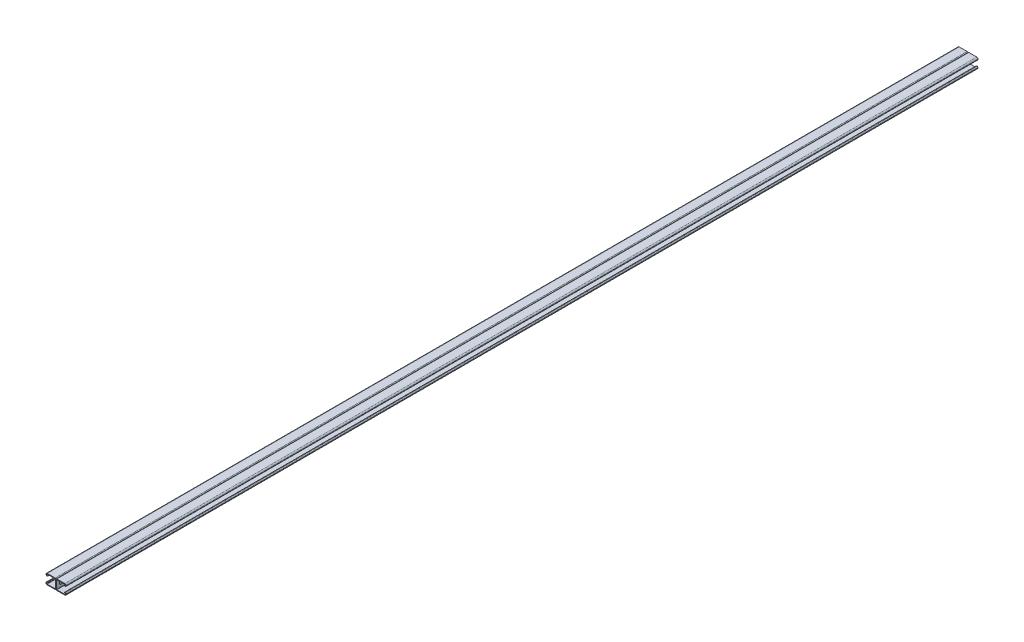
SolidWorks part; units mm, degrees
material "AISI 304"
ref_plane "Front Plane" through (0, 0, 0) normal (0, 0, 1) x (1, 0, 0)
ref_plane "Top Plane" through (0, 0, 0) normal (0, 1, 0) x (1, 0, 0)
ref_plane "Right Plane" through (0, 0, 0) normal (1, 0, 0) x (0, 0, -1)
sketch "Sketch1" plane through (0, 0, 0) normal (0, 0, 1) x (1, 0, 0)
  line L0 (0, 0) -> (-41.275, 0) construction
  line L3 (-41.275, 20.6375) -> (0, 20.6375) construction
  line L4 (-41.275, 20.6375) -> (-41.275, -20.6375) construction
  line L5 (-41.275, -20.6375) -> (0, -20.6375) construction
  line L6 (0, 20.6375) -> (0, -20.6375) construction
  line L7 (-36.2267, 20.6375) -> (-3.4607, 20.6375)
  line L8 (0, 17.1767) -> (0, -17.1767)
  line L9 (-2.794, -17.1767) -> (-2.794, 17.1767)
  line L10 (-3.4607, 17.8435) -> (-36.2267, 17.8435)
  line L11 (-41.275, 15.5892) -> (-41.275, 14.5732)
  line L12 (-37.8142, 11.1125) -> (-35.5346, 11.1125)
  line L14 (-35.5346, 13.9065) -> (-37.8142, 13.9065)
  line L15 (-38.481, 14.5732) -> (-38.481, 15.5892)
  line L16 (-38.481, -14.5733) -> (-38.481, -15.5893)
  line L17 (-35.5346, -13.9065) -> (-37.8142, -13.9065)
  line L18 (-37.8142, -11.1125) -> (-35.5346, -11.1125)
  line L19 (-41.275, -15.5893) -> (-41.275, -14.5733)
  line L20 (-3.4607, -17.8435) -> (-36.2267, -17.8435)
  line L21 (-36.2267, -20.6375) -> (-3.4607, -20.6375)
  line L22 (-2.794, -20.6375) -> (-2.794, 20.6375) construction
  arc A1 (0, 17.1767) -> (-3.4607, 20.6375) centre (-3.4607, 17.1767) ccw
  arc A2 (-2.794, 17.1767) -> (-3.4607, 17.8435) centre (-3.4607, 17.1767) ccw
  arc A4 (-36.2267, 20.6375) -> (-41.275, 15.5892) centre (-36.2267, 15.5892) ccw
  arc A5 (-41.275, 14.5732) -> (-37.8142, 11.1125) centre (-37.8142, 14.5732) ccw
  arc A6 (-35.5346, 11.1125) -> (-35.5346, 13.9065) centre (-35.5346, 12.5095) ccw
  arc A7 (-37.8142, 13.9065) -> (-38.481, 14.5732) centre (-37.8142, 14.5732) cw
  arc A8 (-38.481, 15.5892) -> (-36.2267, 17.8435) centre (-36.2267, 15.5892) cw
  arc A9 (-38.481, -15.5893) -> (-36.2267, -17.8435) centre (-36.2267, -15.5893) ccw
  arc A10 (-37.8142, -13.9065) -> (-38.481, -14.5733) centre (-37.8142, -14.5733) ccw
  arc A11 (-35.5346, -11.1125) -> (-35.5346, -13.9065) centre (-35.5346, -12.5095) cw
  arc A12 (-41.275, -14.5733) -> (-37.8142, -11.1125) centre (-37.8142, -14.5733) cw
  arc A13 (-36.2267, -20.6375) -> (-41.275, -15.5893) centre (-36.2267, -15.5893) cw
  arc A14 (-2.794, -17.1767) -> (-3.4607, -17.8435) centre (-3.4607, -17.1767) cw
  arc A15 (0, -17.1767) -> (-3.4607, -20.6375) centre (-3.4607, -17.1767) cw
  point P24 (0, 20.6375)
  point P65 (-2.794, 0)
  dimension "D1" = 3.4608
  dimension "D2" = 5.0482
  dimension "D3" = 3.4608
  dimension "Ht." = 41.275
  dimension "Wd." = 41.275
  dimension "Thk." = 2.794
  dimension "D4" = 9.525
  dimension "D5" = 7.1374
extrude "Boss-Extrude1" add sketch "Sketch1" against normal blind 3759.2
sketch "Sketch3" plane through (0, 0, 0) normal (1, 0, 0) x (0, 0, -1)
  line L0 (0, 0) -> (3759.2, 0) construction
  point P2 (101.6, 0)
  point P3 (3657.6, 0)
  dimension "D1" = 101.6
  dimension "D2" = 101.6
  dimension "D3" = 3759.2
sketch "Sketch2" plane through (0, 0, 0) normal (1, 0, 0) x (0, 0, -1)
  line L0 (18.2562, 0) -> (32.5437, 0) construction
  line L1 (18.2562, 7.1437) -> (32.5437, 7.1437)
  line L2 (18.2562, -7.1437) -> (32.5437, -7.1437)
  line L3 (18.2562, 0) -> (0, 0) construction
  line L4 (25.4, 0) -> (76.2, 0) construction
  line L5 (0, -17.1767) -> (0, 17.1767) construction
  arc A0 (18.2562, 7.1437) -> (18.2562, -7.1437) centre (18.2562, 0) ccw
  arc A1 (32.5437, -7.1437) -> (32.5437, 7.1437) centre (32.5437, 0) ccw
  point P3 (25.4, 0)
  dimension "Hole to End" = 11.1125
  dimension "D2" = 25.4
extrude "Cut-Extrude1" cut sketch "Sketch2" against normal up to vertex (2.794 mm away) up to point (-2.794, 0, 0)
pattern_linear "LPattern1" count 74 spacing 50.8 along (0, 0, -1) of "Cut-Extrude1"
mirror "Mirror1" about plane through (0, 17.1767, -3759.2) normal (1, 0, 0) of bodies 116
sketch "Sketch4" plane through (0, 20.6375, 0) normal (0, 1, 0) x (1, 0, 0)
  line L1 (-41.275, 0) -> (41.275, 0)
  line L2 (-41.275, 0) -> (-41.275, 2540)
  line L3 (-41.275, 2540) -> (41.275, 2540)
  line L4 (41.275, 0) -> (41.275, 2540)
  line L5 (41.275, 3759.2) -> (41.275, 0) construction
  dimension "D1" = 1219.2
extrude "Cut-Extrude2" [suppressed] cut sketch "Sketch4" against normal through all
equation "\"D1@LPattern1\" = \"Slot Ctr.@Sketch2\""
equation "\"Hole Count@LPattern1\" = \"Lg.@Boss-Extrude1\" / \"D1@LPattern1\""
equation "\"D3@Sketch3\" = \"Lg.@Boss-Extrude1\""
